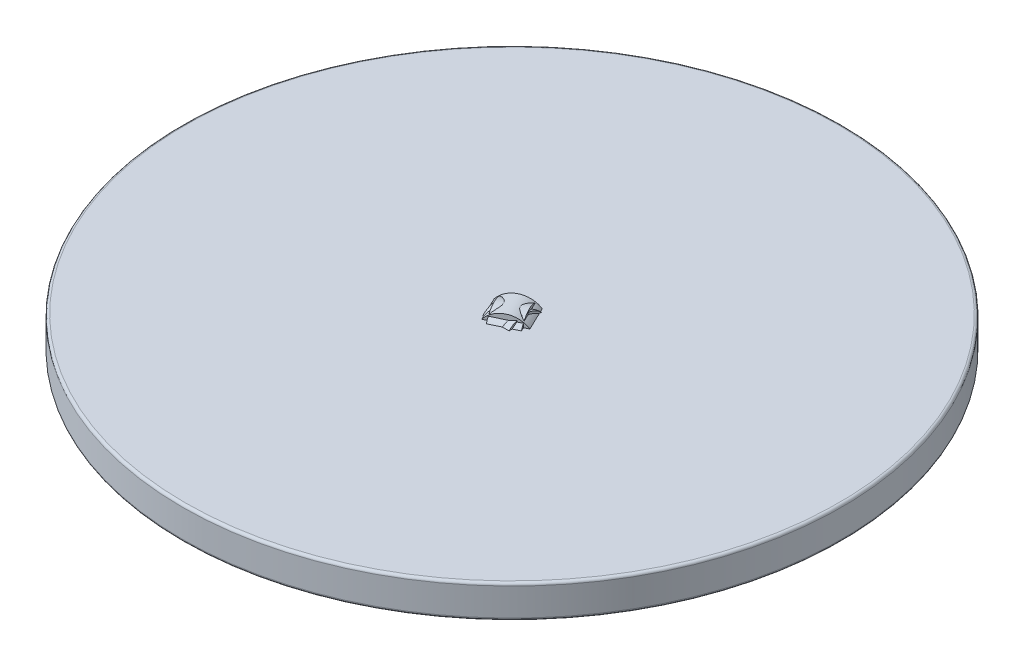
SolidWorks part; units mm, degrees
ref_plane "Front Plane" through (0, 0, 0) normal (0, 0, 1) x (1, 0, 0)
ref_plane "Top Plane" through (0, 0, 0) normal (0, 1, 0) x (1, 0, 0)
ref_plane "Right Plane" through (0, 0, 0) normal (1, 0, 0) x (0, 0, -1)
sketch "Sketch1" plane through (0, 0, 0) normal (0, 1, 0) x (1, 0, 0)
  line L0 (0, 0) -> (0, 250000) construction
  line L1 (0, 0) -> (216506.3509, -125000) construction
  line L2 (0, 0) -> (-216506.3509, -125000) construction
  circle A0 centre (0, 0) radius 250000
  circle A1 centre (-42500, 195000) radius 25000 construction
  circle A2 centre (42500, 195000) radius 25000 construction
  circle A3 centre (190124.9537, -60693.9203) radius 25000 construction
  circle A4 centre (147624.9537, -134306.0797) radius 25000 construction
  circle A5 centre (-147624.9537, -134306.0797) radius 25000 construction
  circle A6 centre (-190124.9537, -60693.9203) radius 25000 construction
  point P18 (0, 0)
  point P21 (0, 0)
  dimension "D1" = 500000
  dimension "D4" = 50000
  dimension "D2" = 85000
  dimension "D3" = 195000
  dimension "D5" = 3
  dimension "D6" = 3
extrude "Boss-Extrude1" add sketch "Sketch1" against normal blind 25000
fillet "Fillet1" radius 2000 2 edges at (0, 0, 250000) (0, -25000, 250000)
sketch "Sketch2" plane through (0, 0, 0) normal (1, 0, 0) x (0, 0, -1)
  line L0 (0, 0) -> (0, -25000) construction
  line L1 (-248000, -25000) -> (248000, -25000) construction
  circle A0 centre (0, -12500) radius 17500
  dimension "D1" = 35000
extrude "Boss-Extrude2" add sketch "Sketch2" along normal mid plane 20000
sketch "Sketch3" plane through (0, 0, 0) normal (0, 1, 0) x (1, 0, 0)
  line L0 (0, 0) -> (29201.9714, -60837.4404) construction
  line L1 (29201.9714, -60837.4404) -> (0, 0) construction
  line L2 (0, 0) -> (43579.6341, 20918.2244) construction
  line L3 (0, 0) -> (-63372.3338, -30418.7202) construction
ref_plane "Plane1" through (0, 0, 0) normal (0.4327, 0, 0.9015) x (0.9015, 0, -0.4327)
sketch "Sketch4" plane through (0, 0, 0) normal (0.4327, 0, 0.9015) x (0.9015, 0, -0.4327)
  line L1 (0, 0) -> (0, -23000) construction
  line L2 (250000, -23000) -> (-250000, -23000) construction
  circle A0 centre (0, -10857.1341) radius 17500
  dimension "D1" = 35000
extrude "Boss-Extrude3" add sketch "Sketch4" along normal mid plane 20000 separate body
ref_plane "Plane2" through (0, 0, 0) normal (0.9015, 0, -0.4327) x (-0.4327, 0, -0.9015)
sketch "Sketch5" plane through (0, 0, 0) normal (0.9015, 0, -0.4327) x (-0.4327, 0, -0.9015)
  line L0 (0, 0) -> (0, -23000) construction
  line L1 (-250000, -23000) -> (250000, -23000) construction
  circle A0 centre (0, -11500) radius 17500
  dimension "D1" = 35000
extrude "Boss-Extrude4" add sketch "Sketch5" along normal mid plane 20000
sketch "Sketch7" plane through (0, -25000, 0) normal (0, 1, 0) x (1, 0, 0)
  line L0 (0, 0) -> (37500, 64951.9053) construction
  line L1 (0, 0) -> (216506.3509, -125000) construction
  line L2 (0, 0) -> (37500, -21650.6351) construction
  dimension "D1" = 75000
